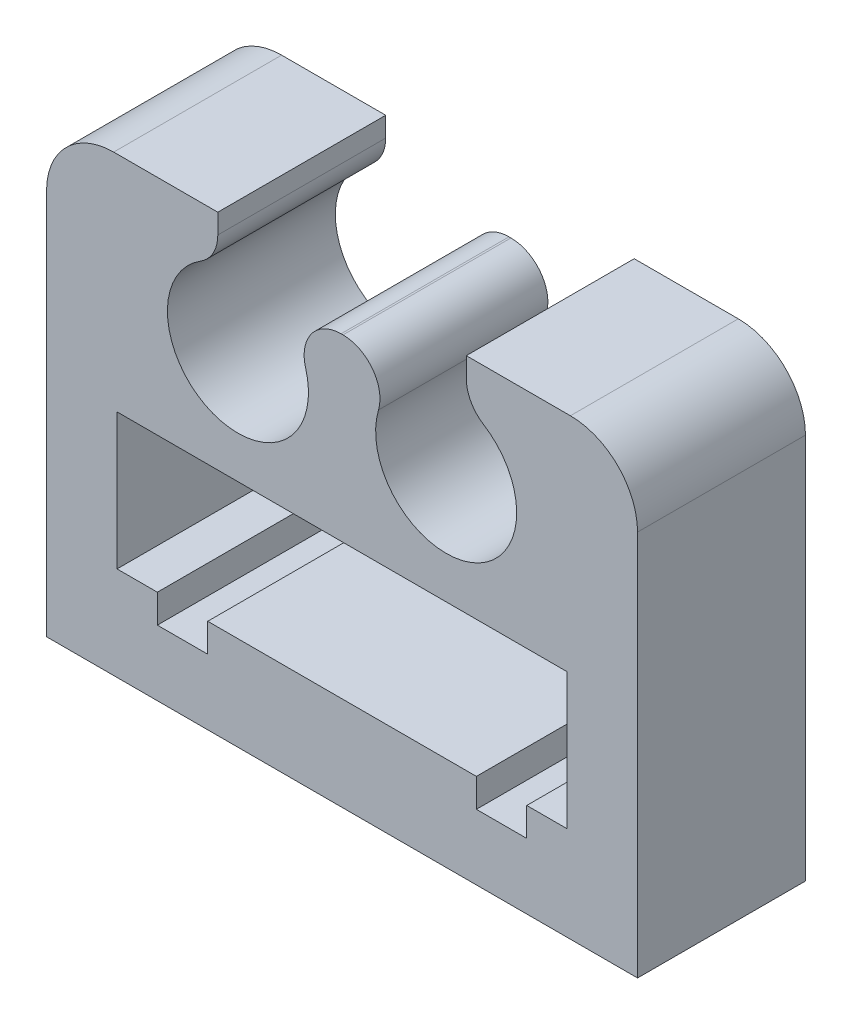
SolidWorks part; units mm, degrees
ref_plane "Front Plane" through (0, 0, 0) normal (0, 0, 1) x (1, 0, 0)
ref_plane "Top Plane" through (0, 0, 0) normal (0, 1, 0) x (1, 0, 0)
ref_plane "Right Plane" through (0, 0, 0) normal (1, 0, 0) x (0, 0, -1)
sketch "Sketch1" plane through (0, 0, 0) normal (0, 0, 1) x (1, 0, 0)
  line L1 (0, 0) -> (17.6, 0)
  line L2 (0, 0) -> (0, 13.5)
  line L3 (0, 13.5) -> (17.6, 13.5)
  line L4 (17.6, 0) -> (17.6, 13.5)
  line L5 (0, 0) -> (17.6, 13.5) construction
  line L6 (0, 13.5) -> (17.6, 0) construction
  point P4 (8.8, 6.75)
  dimension "D1" = 17.6
  dimension "D2" = 13.5
extrude "Boss-Extrude1" add sketch "Sketch1" along normal blind 5
sketch "Sketch2" plane through (0, 0, 5) normal (0, 0, 1) x (1, 0, 0)
  line L0 (8.8, 13.5) -> (8.8, 0) construction
  line L1 (17.6, 13.5) -> (0, 13.5) construction
  line L2 (0, 0) -> (17.6, 0) construction
  line L3 (14.3, 2.8) -> (12.8, 2.8)
  line L4 (2.1, 2.8) -> (15.5, 2.8)
  line L5 (2.1, 2.8) -> (2.1, 6.85)
  line L6 (2.1, 6.85) -> (15.5, 6.85)
  line L7 (15.5, 2.8) -> (15.5, 6.85)
  line L8 (2.1, 2.8) -> (15.5, 6.85) construction
  line L9 (2.1, 6.85) -> (15.5, 2.8) construction
  line L11 (14.3, 2.8) -> (14.3, 1.95)
  line L12 (14.3, 1.95) -> (12.8, 1.95)
  line L13 (12.8, 2.8) -> (12.8, 1.95)
  line L20 (3.3, 2.8) -> (4.8, 2.8)
  line L21 (3.3, 2.8) -> (3.3, 1.95)
  line L22 (3.3, 1.95) -> (4.8, 1.95)
  line L23 (4.8, 2.8) -> (4.8, 1.95)
  line L24 (3.3, 2.8) -> (4.8, 1.95) construction
  line L25 (3.3, 1.95) -> (4.8, 2.8) construction
  point P6 (8.8, 4.825)
  point P11 (0, 0)
  point P12 (3.825, 2.425)
  point P14 (13.204, 7.2336)
  point P24 (4.05, 2.375)
  point P26 (4.3823, 6.85)
  point P27 (4.2881, 6.85)
  point P28 (3.2962, 7.1593)
  dimension "D1" = 13.4
  dimension "D2" = 4.05
  dimension "D3" = 4.9
  dimension "D4" = 1.2
  dimension "D5" = 1.5
  dimension "D6" = 2.8
extrude "Cut-Extrude2" cut sketch "Sketch2" against normal blind 5
sketch "Sketch3" plane through (0, 0, 5) normal (0, 0, 1) x (1, 0, 0)
  line L0 (8.8, 13.5) -> (8.8, 0) construction
  line L1 (17.6, 13.5) -> (0, 13.5) construction
  line L2 (0, 0) -> (17.6, 0) construction
  line L3 (12.5, 13.5) -> (12.5, 12.2)
  line L4 (5.1, 13.5) -> (12.5, 13.5)
  line L5 (5.1, 13.5) -> (5.1, 12.2)
  line L6 (5.1, 12.2) -> (12.5, 12.2)
  line L7 (8.8, 13.5) -> (8.8, 12.2)
  line L8 (5.1, 13.5) -> (8.8, 12.2) construction
  line L9 (5.1, 12.2) -> (8.8, 13.5) construction
  circle A0 centre (5.7, 10.2) radius 2.1
  circle A1 centre (11.9, 10.2) radius 2.1
  point P8 (5.4023, 10.3315)
  point P9 (0, 0)
  point P13 (6.95, 12.85)
  dimension "D1" = 4.2
  dimension "D3" = 0.1
  dimension "D4" = 1
  dimension "D2" = 1.3
  dimension "D5" = 3.7
extrude "Cut-Extrude3" cut sketch "Sketch3" against normal blind 5 contours A0 | L5 L6 L3 L4 | A1
fillet "Fillet1" radius 1.1 4 edges at (6.3403, 12.2, 2.5) (11.2597, 12.2, 2.5) (12.5, 12.2125, 2.5) (5.1, 12.2125, 2.5)
fillet "Fillet2" radius 2 2 edges at (17.6, 13.5, 2.5) (0, 13.5, 2.5)
